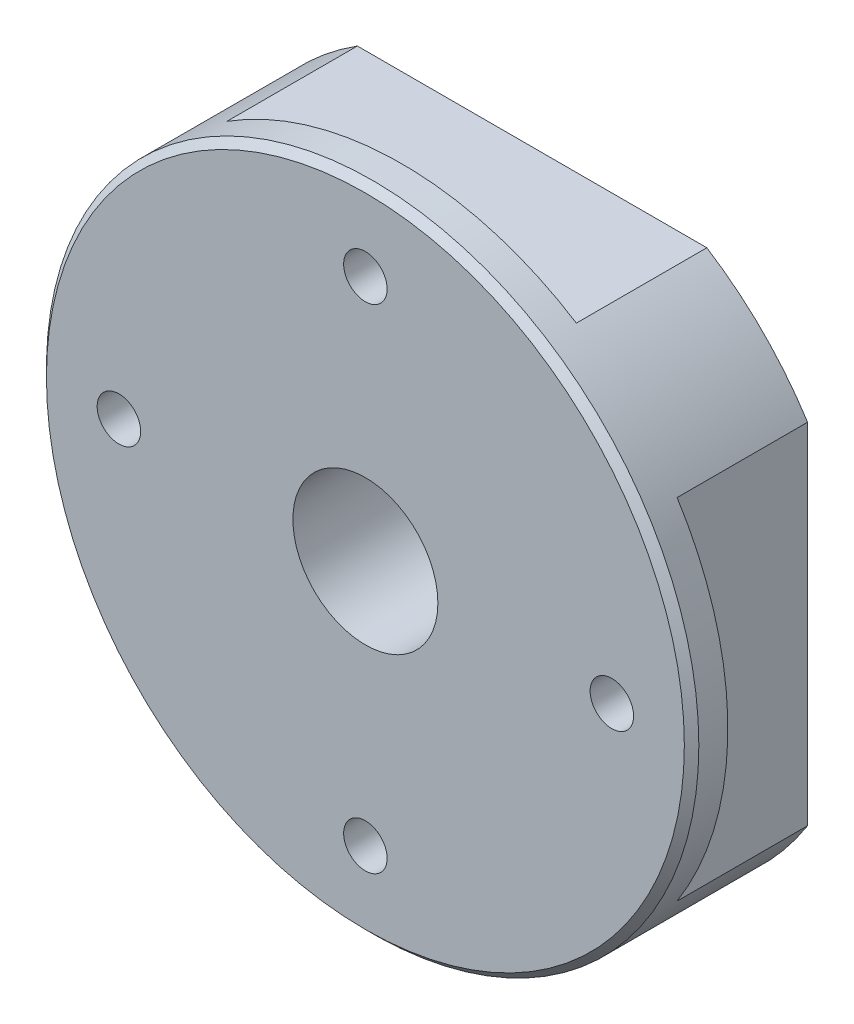
SolidWorks part; units mm, degrees
material "6061 合金"
ref_plane "前视基准面" through (0, 0, 0) normal (0, 0, 1) x (1, 0, 0)
ref_plane "上视基准面" through (0, 0, 0) normal (0, 1, 0) x (1, 0, 0)
ref_plane "右视基准面" through (0, 0, 0) normal (1, 0, 0) x (0, 0, -1)
sketch "草图1" plane through (0, 0, 0) normal (0, 0, 1) x (1, 0, 0)
  circle A0 centre (0, 0) radius 22.5
  circle A1 centre (0, 0) radius 5
  dimension "D1" = 45
  dimension "D2" = 10
extrude "凸台-拉伸1" add sketch "草图1" along normal blind 11.5
sketch "草图2" plane through (0, 0, 11.5) normal (0, 0, 1) x (1, 0, 0)
  circle A0 centre (0, 0) radius 17 construction
  circle A1 centre (0, 17) radius 1.5
  circle A2 centre (17, 0) radius 1.5
  circle A3 centre (0, -17) radius 1.5
  circle A4 centre (-17, 0) radius 1.5
  point P11 (0, 0)
  dimension "D1" = 34
  dimension "D2" = 3
  dimension "D3" = 4
extrude "切除-拉伸1" cut sketch "草图2" against normal blind 5.5
chamfer "倒角1" distance 0.5 angle 45 1 edges at (22.5, 0, 11.5)
sketch "草图3" plane through (0, 0, 0) normal (0, 0, -1) x (-1, 0, 0)
  line L1 (-19, -19) -> (19, -19)
  line L2 (-19, -19) -> (-19, 19)
  line L3 (-19, 19) -> (19, 19)
  line L4 (19, -19) -> (19, 19)
  line L5 (-19, -19) -> (19, 19) construction
  line L6 (-19, 19) -> (19, -19) construction
  point P0 (0, 0)
  dimension "D1" = 38
  dimension "D2" = 38
extrude "切除-拉伸2" cut sketch "草图3" against normal blind 9 flip side to cut
sketch "草图4" plane through (0, 0, 0) normal (0, 0, -1) x (-1, 0, 0)
  line L0 (0, -19) -> (0, 19) construction
  line L1 (-12.052, -19) -> (12.052, -19) construction
  line L2 (12.052, 19) -> (-12.052, 19) construction
  circle A0 centre (0, 0) radius 15.5 construction
  circle A1 centre (0, 15.5) radius 2
  circle A2 centre (0, -15.5) radius 2
  point P9 (0, 15.5)
  point P11 (0, -15.5)
  dimension "D1" = 31
  dimension "D2" = 4
hole_wizard "M4 螺纹孔1" positions "草图4" profile "草图5" tap size "M4" standard "GB"
sketch "草图5" plane through (0, -15.5, 0) normal (1, 0, 0) x (0, 1, 0)
  line L0 (0, 0) -> (0, 3.9914)
  line L1 (0, 3.9914) -> (1.65, 3)
  line L2 (1.65, 3) -> (1.65, 0.375)
  line L3 (1.65, 0.375) -> (2.025, 0)
  line L5 (2.025, 0) -> (0, 0)
  line L6 (-1.65, 0.375) -> (-2.025, 0) construction
  line L10 (0, 3.9914) -> (-1.65, 3) construction
  line L11 (0, -6.35) -> (0, 107.95) construction
  dimension "螺纹孔钻头直径" = 3.3
  dimension "螺纹孔钻头深度" = 3
  dimension "近端锥形沉头孔直径" = 4.05
  dimension "近端锥形沉头孔角度" = 90
  dimension "导头角度" = 118
cosmetic thread "孔螺纹线1" parameters "D1"=3, "D2"=4
cosmetic thread "孔螺纹线2" parameters "D1"=3, "D2"=4
